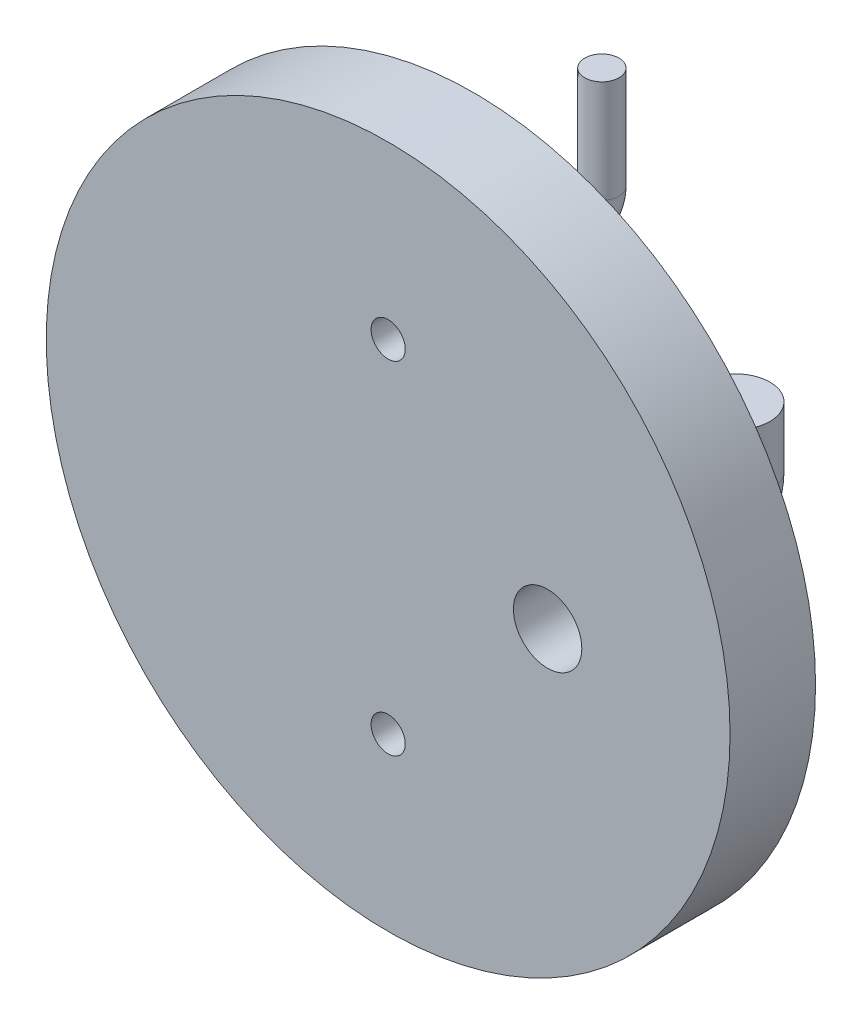
SolidWorks part; units mm, degrees
ref_plane "Front Plane" through (0, 0, 0) normal (0, 0, 1) x (1, 0, 0)
ref_plane "Top Plane" through (0, 0, 0) normal (0, 1, 0) x (1, 0, 0)
ref_plane "Right Plane" through (0, 0, 0) normal (1, 0, 0) x (0, 0, -1)
sketch "Sketch1" plane through (0, 0, 0) normal (0, 0, 1) x (1, 0, 0)
  line L0 (0, -55) -> (0, 55) construction
  circle A0 centre (0, 0) radius 40
  circle A1 centre (0, 20) radius 2
  circle A2 centre (0, -20) radius 2
  circle A3 centre (18.6528, 0) radius 4
  dimension "D1" = 80
  dimension "D2" = 20
  dimension "D3" = 20
extrude "Boss-Extrude1" add sketch "Sketch1" along normal blind 10
sketch "Sketch2" plane through (0, 0, 0) normal (1, 0, 0) x (0, 0, -1)
  line L2 (17, 23) -> (17, 35)
  line L6 (0, 55) -> (0, -55) construction
  line L7 (0, 18) -> (12, 18)
  arc A0 (17, 23) -> (12, 18) centre (12, 23) cw
  dimension "D1" = 5
sketch "Sketch3" plane through (0, 0, 0) normal (0, 0, -1) x (-1, 0, 0)
  circle A0 centre (0, 20) radius 2
sketch "Sketch4" plane through (0, 0, 0) normal (1, 0, 0) x (0, 0, -1)
  line L0 (17, -23) -> (17, -35)
  line L4 (0, 55) -> (0, -55) construction
  line L5 (12, -18) -> (0, -18)
  arc A0 (17, -23) -> (12, -18) centre (12, -23) ccw
  dimension "D1" = 5
sketch "Sketch5" plane through (0, 0, 0) normal (0, 0, 1) x (1, 0, 0)
  circle A0 centre (0, -20) radius 2
sweep "Sweep4" add profiles "Sketch5" path "Sketch4"
sweep "Sweep5" add profiles "Sketch3" path "Sketch2"
sketch "Sketch6" plane through (0, 0, 0) normal (0, 0, 1) x (1, 0, 0)
  circle A0 centre (18.6528, 0) radius 4
ref_plane "Plane1" through (18.6528, 0, 0) normal (1, 0, 0) x (0, 0, -1)
sketch "Sketch8" plane through (18.6528, 0, 0) normal (1, 0, 0) x (0, 0, -1)
  line L0 (0, 0) -> (7, 0)
  line L1 (14.85, 0) -> (-14.85, 0) construction
  line L2 (12, 5) -> (12, 12)
  arc A0 (12, 5) -> (7, 0) centre (7, 5) cw
  point P8 (12, 0)
  dimension "D1" = 5
sweep "Sweep6" add profiles "Sketch6" path "Sketch8"
